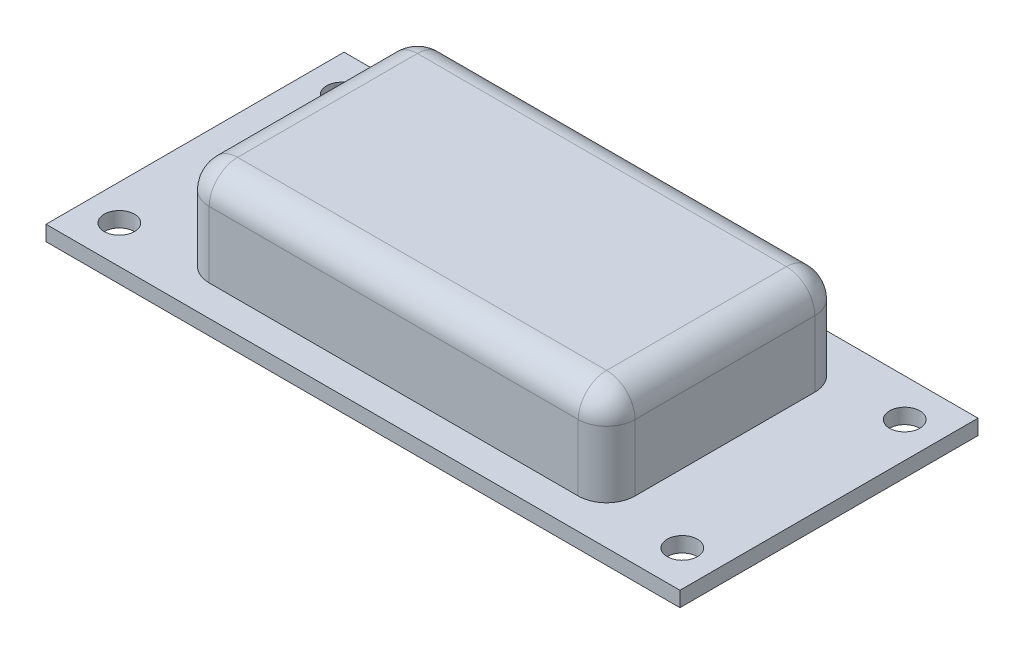
SolidWorks part; units mm, degrees
ref_plane "前基準面" through (0, 0, 0) normal (0, 0, 1) x (1, 0, 0)
ref_plane "上基準面" through (0, 0, 0) normal (0, 1, 0) x (1, 0, 0)
ref_plane "右基準面" through (0, 0, 0) normal (1, 0, 0) x (0, 0, -1)
sketch "草圖1" plane through (0, 0, 0) normal (0, 1, 0) x (1, 0, 0)
  line L1 (-33.5, -15.75) -> (33.5, -15.75)
  line L2 (-33.5, -15.75) -> (-33.5, 15.75)
  line L3 (-33.5, 15.75) -> (33.5, 15.75)
  line L4 (33.5, -15.75) -> (33.5, 15.75)
  line L5 (-33.5, -15.75) -> (33.5, 15.75) construction
  line L6 (-33.5, 15.75) -> (33.5, -15.75) construction
  line L7 (-29.75, -11.75) -> (29.75, -11.75) construction
  line L8 (-29.75, -11.75) -> (-29.75, 11.75) construction
  line L9 (-29.75, 11.75) -> (29.75, 11.75) construction
  line L10 (29.75, -11.75) -> (29.75, 11.75) construction
  line L11 (-29.75, -11.75) -> (29.75, 11.75) construction
  line L12 (-29.75, 11.75) -> (29.75, -11.75) construction
  circle A0 centre (-29.75, 11.75) radius 1.6
  circle A1 centre (-29.75, -11.75) radius 1.6
  circle A2 centre (29.75, -11.75) radius 1.6
  circle A3 centre (29.75, 11.75) radius 1.6
  point P0 (0, 0)
  point P6 (0, 0)
  dimension "D5" = 3.2
  dimension "D1" = 67
  dimension "D2" = 31.5
  dimension "D3" = 59.5
  dimension "D4" = 23.5
extrude "填料-伸長1" add sketch "草圖1" along normal blind 1.6
sketch "草圖2" plane through (0, 1.6, 0) normal (0, 1, 0) x (1, 0, 0)
  line L1 (-22.5, -12.5) -> (22.5, -12.5)
  line L2 (-22.5, -12.5) -> (-22.5, 12.5)
  line L3 (-22.5, 12.5) -> (22.5, 12.5)
  line L4 (22.5, -12.5) -> (22.5, 12.5)
  line L5 (-22.5, -12.5) -> (22.5, 12.5) construction
  line L6 (-22.5, 12.5) -> (22.5, -12.5) construction
  point P0 (0, 0)
  dimension "D1" = 45
  dimension "D2" = 25
extrude "填料-伸長2" add sketch "草圖2" along normal blind 10
fillet "圓角1" radius 3 8 edges at (22.5, 11.6, 0) (0, 11.6, -12.5) (0, 11.6, 12.5) (-22.5, 11.6, 0) (-22.5, 6.6, 12.5) (22.5, 6.6, 12.5) (22.5, 6.6, -12.5) (-22.5, 6.6, -12.5)
